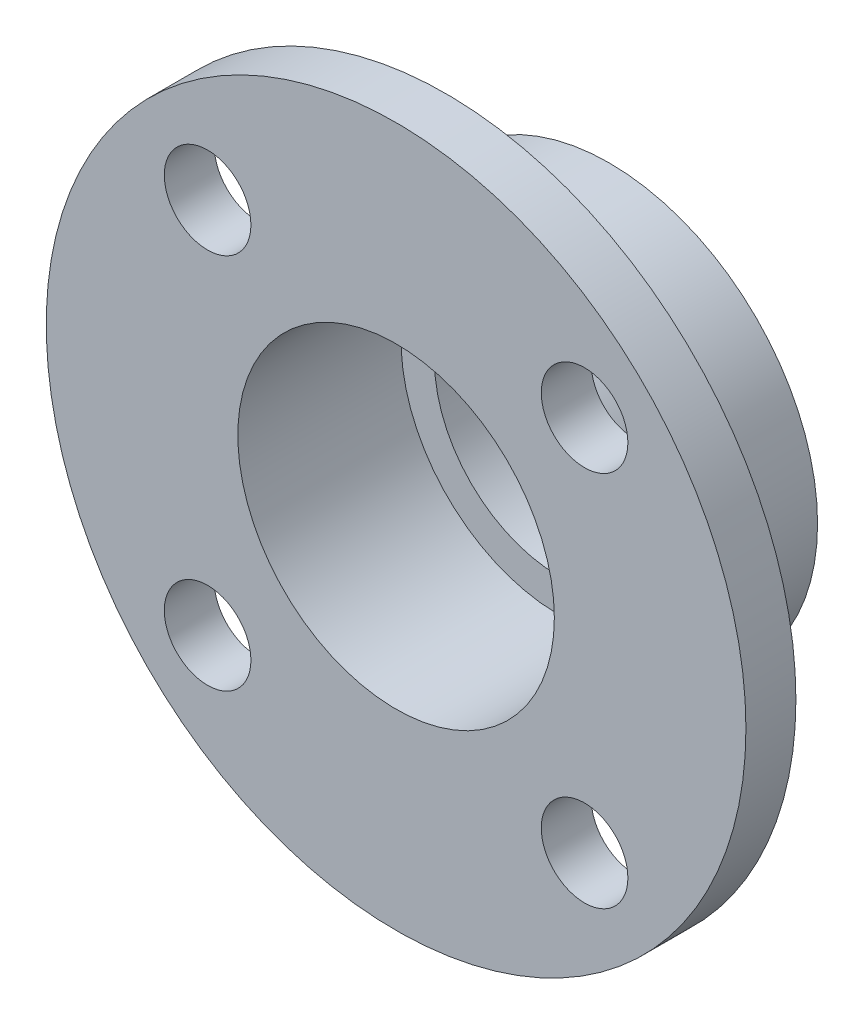
SolidWorks part; units mm, degrees
ref_plane "Спереди" through (0, 0, 0) normal (0, 0, 1) x (1, 0, 0)
ref_plane "Сверху" through (0, 0, 0) normal (0, 1, 0) x (1, 0, 0)
ref_plane "Справа" through (0, 0, 0) normal (1, 0, 0) x (0, 0, -1)
sketch "Эскиз1" plane through (0, 0, 0) normal (0, 1, 0) x (1, 0, 0)
  line L0 (-9.5, 0) -> (-21, 0)
  line L1 (-21, 0) -> (-21, 3)
  line L2 (-21, 3) -> (-12.5, 3)
  line L3 (-12.5, 3) -> (-12.5, 12.8)
  line L4 (-12.5, 12.8) -> (-7.5, 12.8)
  line L5 (-7.5, 12.8) -> (-7.5, 9.8)
  line L6 (-7.5, 9.8) -> (-9.5, 9.8)
  line L7 (-9.5, 9.8) -> (-9.5, 0)
  line L8 (0, 0) -> (0, 23135.1827) construction
  dimension "D1" = 7.5
  dimension "D2" = 9.5
  dimension "D3" = 21
  dimension "D4" = 3
  dimension "D5" = 3
  dimension "D6" = 3
  dimension "D7" = 12.8
revolve "Повернуть1" add sketch "Эскиз1" angle 360 about L8
sketch "Эскиз2" plane through (0, 0, 0) normal (0, 0, 1) x (1, 0, 0)
  line L0 (0, 0) -> (0, 21) construction
  circle A0 centre (11.3137, 11.3137) radius 2.6
  circle A1 centre (0, 0) radius 21 construction
  dimension "D1" = 5.2
  dimension "D2" = 45
  dimension "D3" = 16
extrude "Вырез-Вытянуть1" cut sketch "Эскиз2" against normal up to surface (3 mm away) up to face at (21, 0, -3)
pattern_circular "Круговой массив1" count 4 over 360 about axis through (0, 0, 0) along (0, 0, 1) of "Вырез-Вытянуть1"
